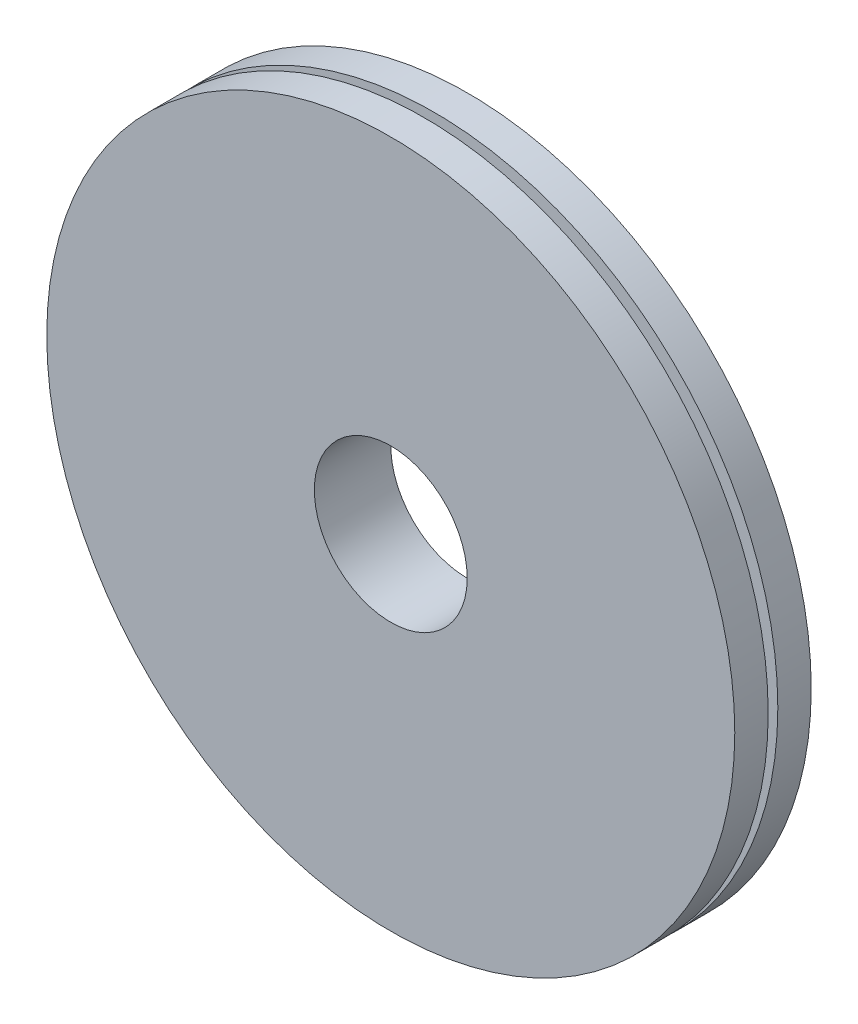
SolidWorks part; units mm, degrees
ref_plane "Front Plane" through (0, 0, 0) normal (0, 0, 1) x (1, 0, 0)
ref_plane "Top Plane" through (0, 0, 0) normal (0, 1, 0) x (1, 0, 0)
ref_plane "Right Plane" through (0, 0, 0) normal (1, 0, 0) x (0, 0, -1)
sketch "Sketch1" plane through (0, 0, 0) normal (0, 0, 1) x (1, 0, 0)
  circle A0 centre (0, 0) radius 57.15
  circle A1 centre (0, 0) radius 12.7
  dimension "D1" = 114.3
  dimension "D2" = 25.4
extrude "Boss-Extrude1" add sketch "Sketch1" along normal blind 12.7
ref_plane "Plane1" through (0, 0, 6.35) normal (0, 0, -1) x (-1, 0, 0)
sketch "Sketch3" plane through (0, 0, 6.35) normal (0, 0, -1) x (-1, 0, 0)
  circle A0 centre (0, 0) radius 53.975
  circle A1 centre (0, 0) radius 57.15
  circle A2 centre (0, 0) radius 57.15
  dimension "D2" = 107.95
  dimension "D1" = 0
extrude "Cut-Extrude1" cut sketch "Sketch3" against normal mid plane 1.6002
equation "\"Cutter_OD\"=4.5"
equation "\"D1@Sketch1\"=\"Cutter_OD\""
equation "\"Cutter_ID\"=1"
equation "\"D2@Sketch1\"=\"Cutter_ID\""
